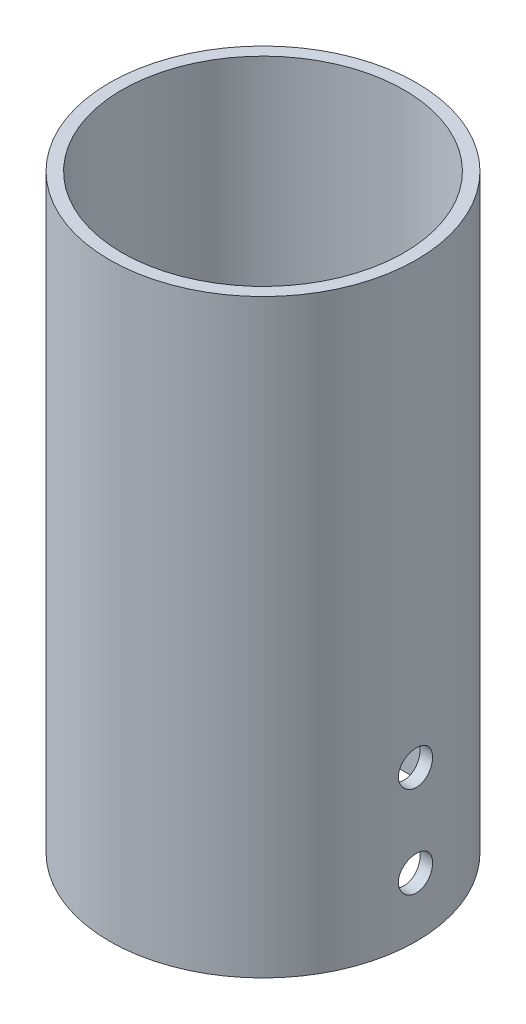
SolidWorks part; units mm, degrees
ref_plane "Front Plane" through (0, 0, 0) normal (0, 0, 1) x (1, 0, 0)
ref_plane "Top Plane" through (0, 0, 0) normal (0, 1, 0) x (1, 0, 0)
ref_plane "Right Plane" through (0, 0, 0) normal (1, 0, 0) x (0, 0, -1)
sketch "Sketch1" plane through (0, 0, 0) normal (0, 1, 0) x (1, 0, 0)
  circle A0 centre (0, 0) radius 26
  circle A1 centre (0, 0) radius 23.9
  dimension "D1" = 52
  dimension "D2" = 47.8
extrude "Boss-Extrude1" add sketch "Sketch1" along normal blind 100
sketch "Sketch2" plane through (0, 0, 0) normal (1, 0, 0) x (0, 0, -1)
  line L0 (0, 0) -> (0, 10)
  line L1 (0, 10) -> (0, 25.5)
  circle A0 centre (0, 10) radius 2.9
  circle A1 centre (0, 25.5) radius 2.9
  dimension "D1" = 5.8
  dimension "D2" = 5.8
  dimension "D3" = 10
  dimension "D4" = 15.5
extrude "Cut-Extrude1" cut sketch "Sketch2" against normal through all both and the other way through all
equation "\"TubeOutsideDiameter\"= 52"
equation "\"D1@Sketch1\"=\"TubeOutsideDiameter\""
equation "\"TubeInnerDiameter\"= 47.8"
equation "\"ReleaseMechanisumHeight\"=100"
equation "\"WireDiameter\"=3.38983"
equation "\"servoHoleDiameter\"= 2.8"
equation "\"CordDiameter\"= 5"
equation "\"MountingBoldDiameter\"=2.8"
equation "\"TubeMountingBoltDiameter\"= 5"
equation "\"D2@Sketch1\"=\"TubeInnerDiameter\""
equation "\"CardTubeOutsideDiameter\"= 54.2"
equation "\"CardTubeInsideDiameter\"= 50.4"
equation "\"D1@Sketch2\"=\"TubeMountingBoltDiameter\"+0.8"
equation "\"D2@Sketch2\"=\"TubeMountingBoltDiameter\"+0.8"
equation "\"TubeInsideDiameter\"=94.6721"
equation "\"FinnHeight\"= 190"
equation "\"MountingBoltDiameter\"=11.1313"
equation "\"FinnWidth\"=60"
